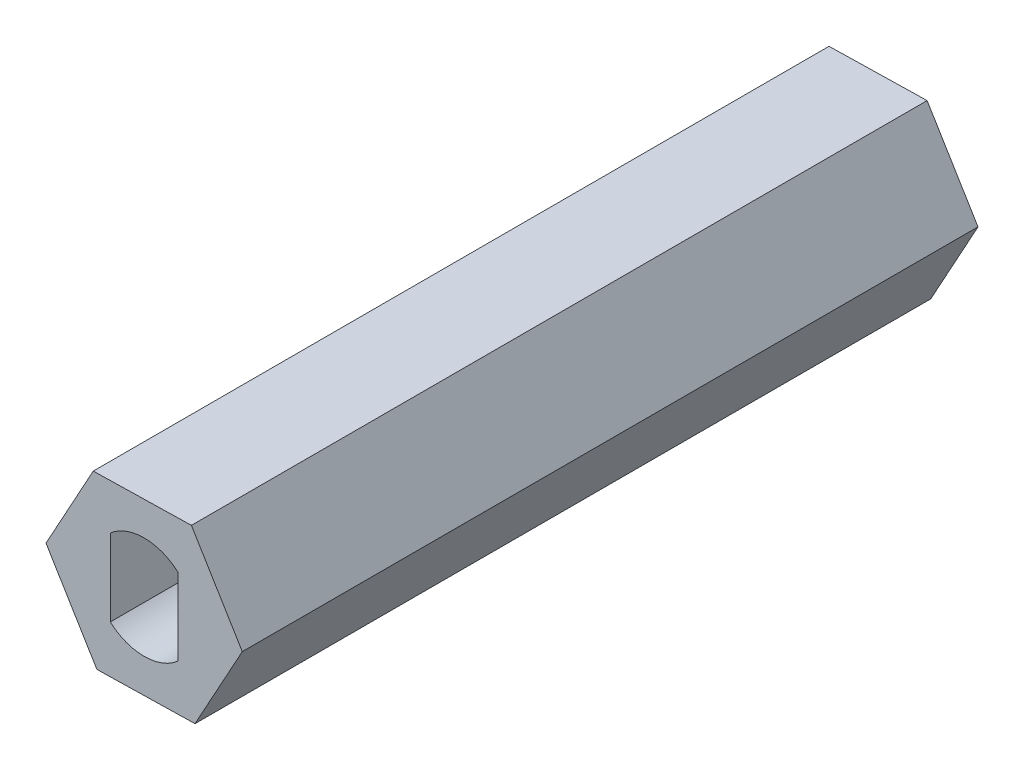
SolidWorks part; units mm, degrees
ref_plane "Front Plane" through (0, 0, 0) normal (0, 0, 1) x (1, 0, 0)
ref_plane "Top Plane" through (0, 0, 0) normal (0, 1, 0) x (1, 0, 0)
ref_plane "Right Plane" through (0, 0, 0) normal (1, 0, 0) x (0, 0, -1)
sketch "Sketch1" plane through (0, 0, 0) normal (0, 0, 1) x (1, 0, 0)
  line L1 (2.4415, 4.4434) -> (-2.6274, 4.3361)
  line L2 (-2.6274, 4.3361) -> (-5.0689, -0.1074)
  line L3 (-5.0689, -0.1074) -> (-2.4415, -4.4434)
  line L4 (-2.4415, -4.4434) -> (2.6274, -4.3361)
  line L5 (2.6274, -4.3361) -> (5.0689, 0.1074)
  line L6 (5.0689, 0.1074) -> (2.4415, 4.4434)
  line L8 (1.75, 2.0048) -> (1.75, -1.9752)
  line L10 (-1.75, 2.0048) -> (-1.75, -1.9752)
  circle A0 centre (0, 0) radius 4.3907 construction
  arc A1 (1.75, 2.0048) -> (-1.75, 2.0048) centre (0, 0) ccw
  arc A2 (1.75, -1.9752) -> (-1.75, -1.9752) centre (0, 0) cw
  dimension "D1" = 3.98
  dimension "D2" = 3.5
  dimension "D3" = 1.75
  dimension "D4" = 5.07
extrude "Boss-Extrude1" add sketch "Sketch1" along normal blind 8
sketch "Sketch2" plane through (0, 0, 0) normal (0, 0, -1) x (-1, 0, 0)
  line L1 (2.6274, 4.3361) -> (-2.4415, 4.4434)
  line L2 (-2.4415, 4.4434) -> (-5.0689, 0.1074)
  line L3 (-5.0689, 0.1074) -> (-2.6274, -4.3361)
  line L4 (-2.6274, -4.3361) -> (2.4415, -4.4434)
  line L5 (2.4415, -4.4434) -> (5.0689, -0.1074)
  line L6 (5.0689, -0.1074) -> (2.6274, 4.3361)
  circle A0 centre (0, 0) radius 4.3907 construction
  dimension "D1" = 5.07
extrude "Boss-Extrude2" add sketch "Sketch2" along normal blind 30
